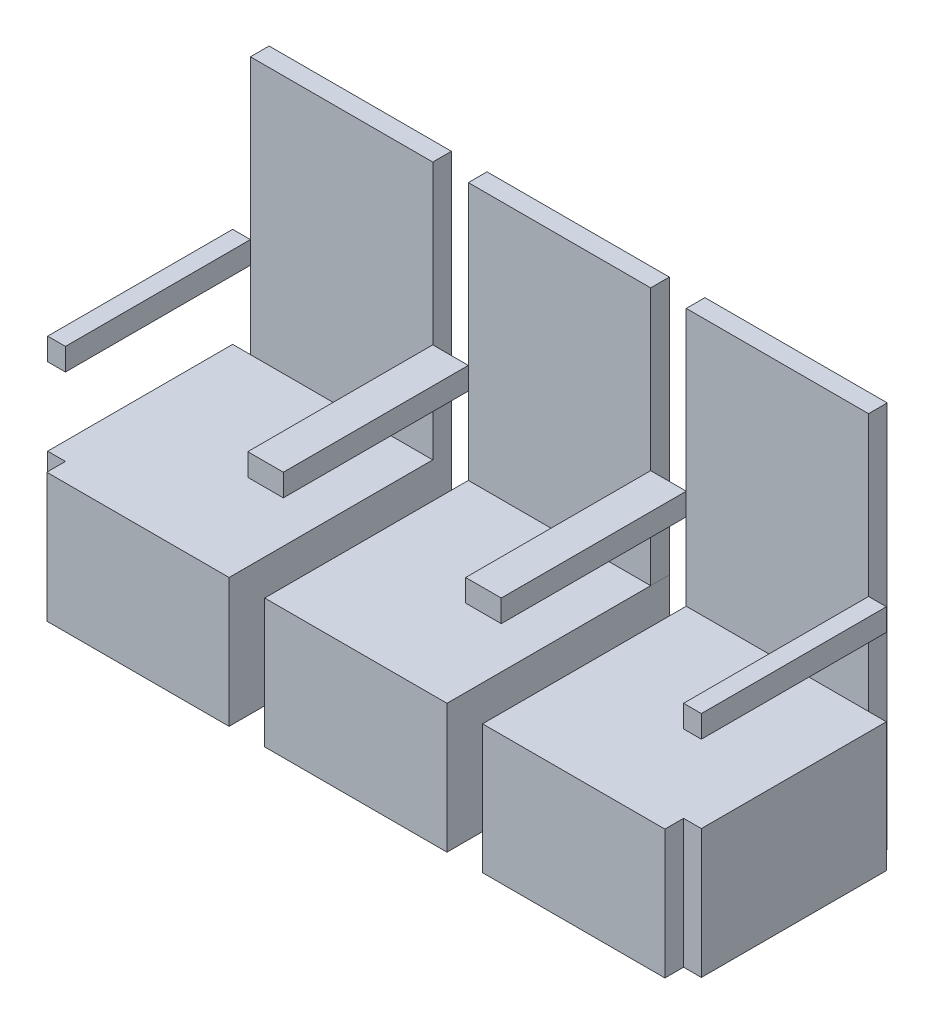
SolidWorks part; units mm, degrees
ref_plane "Front Plane" through (0, 0, 0) normal (0, 0, 1) x (1, 0, 0)
ref_plane "Top Plane" through (0, 0, 0) normal (0, 1, 0) x (1, 0, 0)
ref_plane "Right Plane" through (0, 0, 0) normal (1, 0, 0) x (0, 0, -1)
sketch "Sketch1" plane through (0, 0, 0) normal (0, 1, 0) x (1, 0, 0)
  line L0 (0, -55) -> (0, 55) construction
  line L13 (-933.45, 264.16) -> (-882.65, 264.16)
  line L14 (-882.65, 317.5) -> (-361.95, 317.5)
  line L15 (-933.45, 264.16) -> (-933.45, -264.16)
  line L16 (-882.65, -317.5) -> (-361.95, -317.5)
  line L17 (-361.95, 317.5) -> (-361.95, -317.5)
  line L18 (361.95, -317.5) -> (882.65, -317.5)
  line L19 (361.95, -317.5) -> (361.95, 317.5)
  line L20 (361.95, 317.5) -> (882.65, 317.5)
  line L21 (933.45, -264.16) -> (933.45, 264.16)
  line L22 (-882.65, 264.16) -> (-882.65, 317.5)
  line L23 (882.65, 264.16) -> (882.65, 317.5)
  line L24 (933.45, 264.16) -> (882.65, 264.16)
  line L25 (-55, 0) -> (55, 0) construction
  line L26 (882.65, -264.16) -> (882.65, -317.5)
  line L27 (-882.65, -264.16) -> (-882.65, -317.5)
  line L28 (-933.45, -264.16) -> (-882.65, -264.16)
  line L29 (933.45, -264.16) -> (882.65, -264.16)
  line L31 (-260.35, 317.5) -> (260.35, 317.5)
  line L32 (-260.35, 317.5) -> (-260.35, -317.5)
  line L33 (-260.35, -317.5) -> (260.35, -317.5)
  line L34 (260.35, 317.5) -> (260.35, -317.5)
  point P8 (-361.95, 0)
  point P9 (361.95, 0)
  point P30 (0, 317.5)
  dimension "D1" = 1866.9
  dimension "D3" = 50.8
  dimension "D4" = 53.34
  dimension "D5" = 635
  dimension "D7" = 520.7
extrude "Boss-Extrude1" add sketch "Sketch1" along normal blind 368.3
sketch "Sketch2" plane through (0, 368.3, 0) normal (0, 1, 0) x (1, 0, 0)
  line L0 (0, -55) -> (0, 55) construction
  line L1 (-882.65, 264.16) -> (-361.95, 264.16)
  line L2 (-882.65, 264.16) -> (-882.65, 317.5)
  line L3 (-882.65, 317.5) -> (-361.95, 317.5)
  line L4 (-361.95, 264.16) -> (-361.95, 317.5)
  line L5 (882.65, 317.5) -> (361.95, 317.5)
  line L6 (361.95, 264.16) -> (361.95, 317.5)
  line L7 (882.65, 264.16) -> (361.95, 264.16)
  line L8 (882.65, 264.16) -> (882.65, 317.5)
  line L9 (260.35, -317.5) -> (260.35, 317.5) construction
  line L10 (-260.35, 317.5) -> (260.35, 317.5)
  line L11 (-260.35, 317.5) -> (-260.35, 264.16)
  line L12 (-260.35, 264.16) -> (260.35, 264.16)
  line L13 (260.35, 317.5) -> (260.35, 264.16)
extrude "Boss-Extrude2" add sketch "Sketch2" along normal blind 736.6
sketch "Sketch3" plane through (0, 0, -264.16) normal (0, 0, 1) x (1, 0, 0)
  line L0 (-882.65, 1104.9) -> (-882.65, 368.3) construction
  line L1 (-882.65, 589.28) -> (-933.45, 589.28)
  line L2 (-882.65, 589.28) -> (-882.65, 652.78)
  line L3 (-882.65, 652.78) -> (-933.45, 652.78)
  line L4 (-933.45, 589.28) -> (-933.45, 652.78)
  line L5 (-933.45, 368.3) -> (-882.65, 368.3) construction
  line L6 (0, -55) -> (0, 55) construction
  line L7 (882.65, 652.78) -> (933.45, 652.78)
  line L8 (933.45, 589.28) -> (933.45, 652.78)
  line L9 (882.65, 589.28) -> (933.45, 589.28)
  line L10 (882.65, 589.28) -> (882.65, 652.78)
  line L11 (-361.95, 1104.9) -> (-361.95, 368.3) construction
  line L12 (-361.95, 589.28) -> (-260.35, 589.28)
  line L13 (-361.95, 589.28) -> (-361.95, 652.78)
  line L14 (-361.95, 652.78) -> (-260.35, 652.78)
  line L15 (361.95, 589.28) -> (361.95, 652.78)
  line L16 (361.95, 1104.9) -> (361.95, 368.3) construction
  line L17 (-260.35, 589.28) -> (-260.35, 652.78)
  line L18 (-260.35, 1104.9) -> (-260.35, 368.3) construction
  line L19 (260.35, 652.78) -> (260.35, 589.28)
  line L20 (260.35, 1104.9) -> (260.35, 368.3) construction
  line L21 (260.35, 652.78) -> (361.95, 652.78)
  line L22 (260.35, 589.28) -> (361.95, 589.28)
  dimension "D1" = 63.5
  dimension "D2" = 220.98
extrude "Boss-Extrude3" add sketch "Sketch3" along normal up to surface (528.32 mm away) separate body up to face at (-908.05, 184.15, 264.16)
